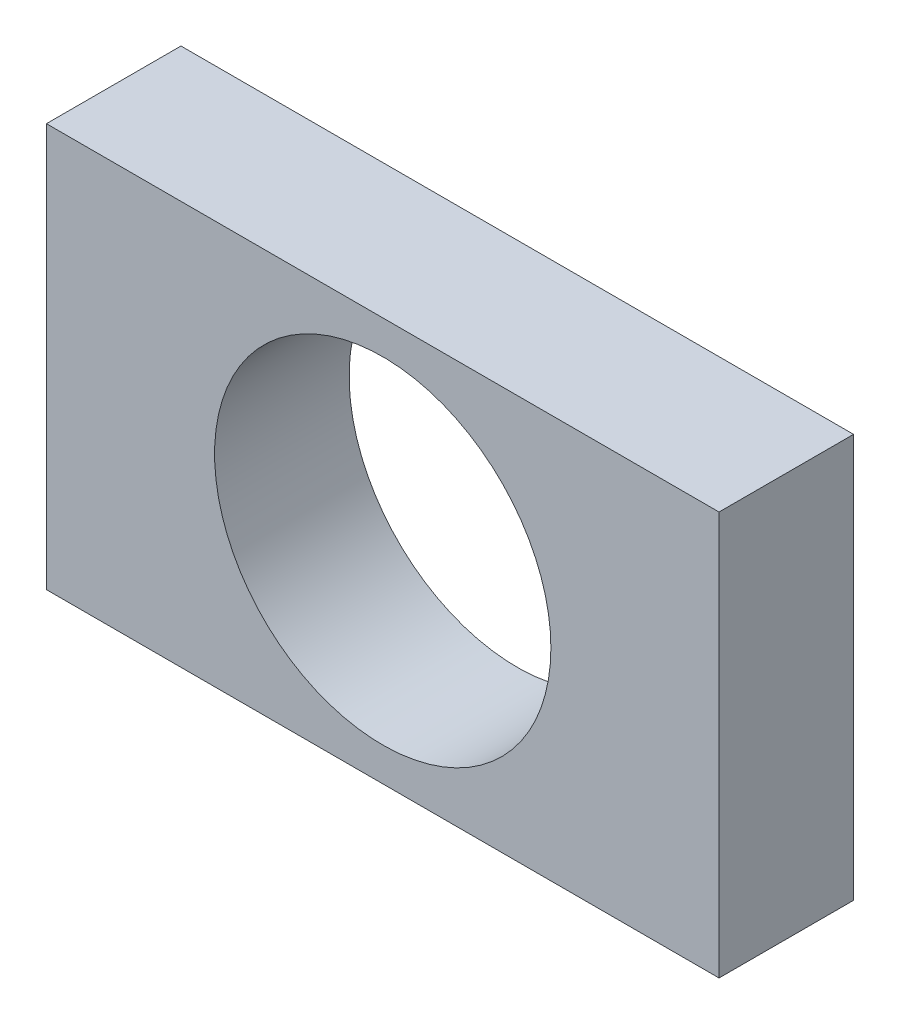
SolidWorks part; units mm, degrees
ref_plane "Спереди" through (0, 0, 0) normal (0, 0, 1) x (1, 0, 0)
ref_plane "Сверху" through (0, 0, 0) normal (0, 1, 0) x (1, 0, 0)
ref_plane "Справа" through (0, 0, 0) normal (1, 0, 0) x (0, 0, -1)
sketch "Эскиз1" plane through (0, 0, 0) normal (0, 0, 1) x (1, 0, 0)
  line L1 (-50, -30) -> (50, -30)
  line L2 (-50, -30) -> (-50, 30)
  line L3 (-50, 30) -> (50, 30)
  line L4 (50, -30) -> (50, 30)
  line L5 (0, 30) -> (0, -30) construction
  line L6 (-50, 0) -> (50, 0) construction
  circle A0 centre (0, 0) radius 25
  point P0 (0, 0)
  dimension "D1" = 100
  dimension "D2" = 60
extrude "Бобышка-Вытянуть1" add sketch "Эскиз1" along normal blind 20
